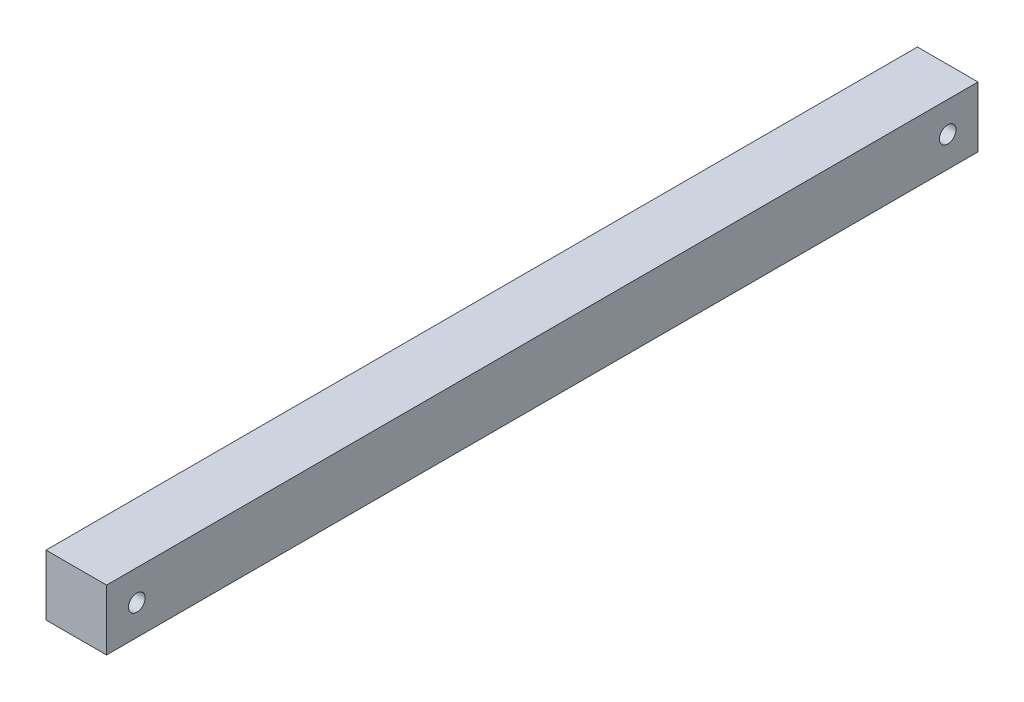
SolidWorks part; units mm, degrees
ref_plane "Front Plane" through (0, 0, 0) normal (0, 0, 1) x (1, 0, 0)
ref_plane "Top Plane" through (0, 0, 0) normal (0, 1, 0) x (1, 0, 0)
ref_plane "Right Plane" through (0, 0, 0) normal (1, 0, 0) x (0, 0, -1)
sketch "Sketch1" plane through (0, 0, 0) normal (0, 0, 1) x (1, 0, 0)
  line L5 (-12.7, -12.7) -> (12.7, -12.7)
  line L6 (-12.7, -12.7) -> (-12.7, 12.7)
  line L7 (-12.7, 12.7) -> (12.7, 12.7)
  line L8 (12.7, -12.7) -> (12.7, 12.7)
  line L9 (-12.7, -12.7) -> (12.7, 12.7) construction
  line L10 (-12.7, 12.7) -> (12.7, -12.7) construction
  point P0 (0, 0)
  dimension "D1" = 25.4
  dimension "D2" = 25.4
extrude "Boss-Extrude1" add sketch "Sketch1" along normal blind 365.4
sketch "Sketch10" plane through (-12.7, 0, 0) normal (-1, 0, 0) x (0, 0, 1)
  line L0 (182.7, 12.7) -> (182.7, 75.2381) construction
  line L1 (365.4, 12.7) -> (0, 12.7) construction
  line L2 (365.4, 12.7) -> (365.4, -12.7) construction
  circle A0 centre (352.7, 0) radius 3.5
  circle A1 centre (12.7, 0) radius 3.5
  dimension "D1" = 7
  dimension "D3" = 12.7
  dimension "D2" = 12.7
extrude "Cut-Extrude6" cut sketch "Sketch10" against normal through all
